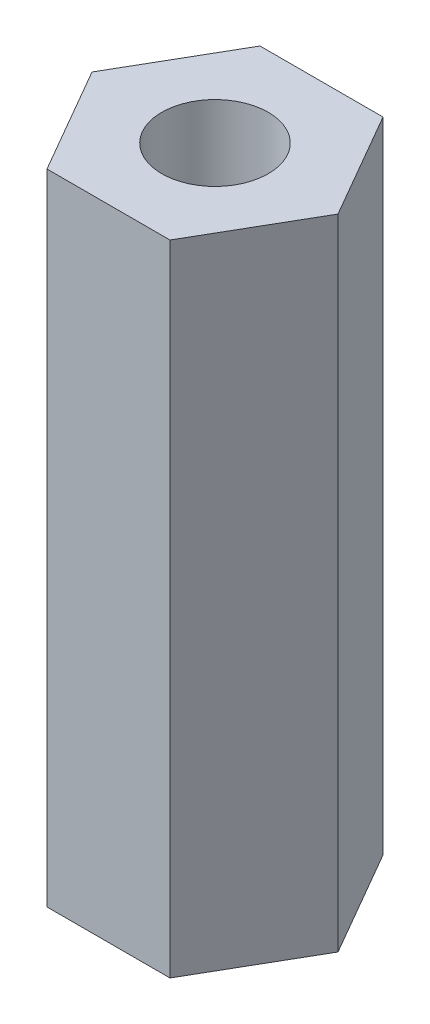
SolidWorks part; units mm, degrees
ref_plane "Front Plane" through (0, 0, 0) normal (0, 0, 1) x (1, 0, 0)
ref_plane "Top Plane" through (0, 0, 0) normal (0, 1, 0) x (1, 0, 0)
ref_plane "Right Plane" through (0, 0, 0) normal (1, 0, 0) x (0, 0, -1)
sketch "Sketch1" plane through (0, 0, 0) normal (0, 1, 0) x (1, 0, 0)
  line L1 (7.3323, 0) -> (3.6662, 6.35)
  line L2 (3.6662, 6.35) -> (-3.6662, 6.35)
  line L3 (-3.6662, 6.35) -> (-7.3323, 0)
  line L4 (-7.3323, 0) -> (-3.6662, -6.35)
  line L5 (-3.6662, -6.35) -> (3.6662, -6.35)
  line L6 (3.6662, -6.35) -> (7.3323, 0)
  circle A1 centre (0, 0) radius 3.175
  circle A2 centre (0, 0) radius 6.35 construction
extrude "Boss-Extrude1" add sketch "Sketch1" along normal blind 38.1
